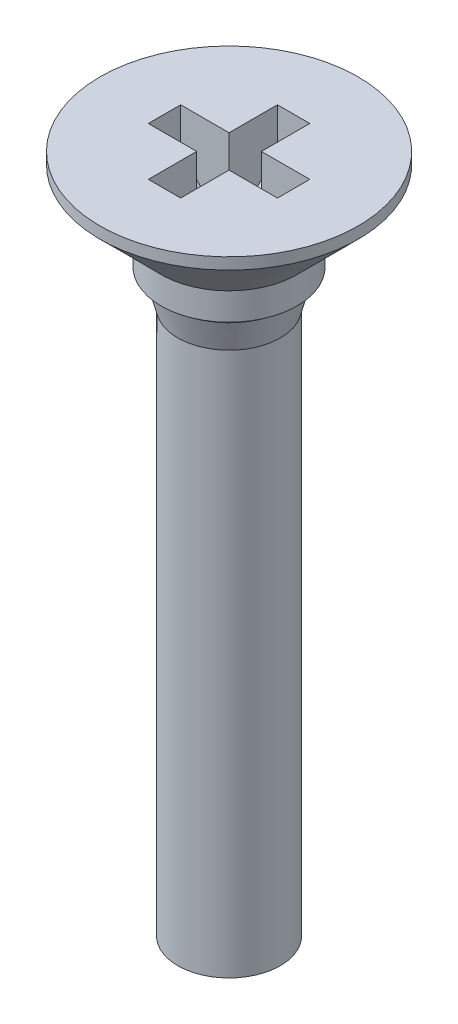
SolidWorks part; units mm, degrees
ref_plane "Vorderseite" through (0, 0, 0) normal (0, 0, 1) x (1, 0, 0)
ref_plane "Oben" through (0, 0, 0) normal (0, 1, 0) x (1, 0, 0)
ref_plane "Rechts" through (0, 0, 0) normal (1, 0, 0) x (0, 0, -1)
sketch "Skizze1" plane through (0, 0, 0) normal (0, 0, 1) x (1, 0, 0)
  line L0 (0, 0) -> (1.9, 0)
  line L1 (1.9, 0) -> (1.9, -0.17)
  line L2 (1.9, -0.17) -> (1, -1.07)
  line L3 (0.87, -1.47) -> (0.87, -1.5689)
  line L4 (0.87, -1.5689) -> (0.7545, -2)
  line L5 (0.7545, -2) -> (0.7545, -10)
  line L6 (0.7545, -10) -> (0, -10)
  line L7 (0, 0) -> (0, -10) construction
  line L8 (0, 0) -> (0, -10)
  line L10 (1, -1.07) -> (1, -1.47)
  line L12 (1, -1.47) -> (0.87, -1.47)
  point P3 (0.87, -1.2)
  dimension "D1" = 45
  dimension "D2" = 15
  dimension "K" = 1.2
  dimension "DA" = 3.8
  dimension "DK" = 1.509
  dimension "L" = 10
  dimension "DG" = 2
  dimension "A" = 0.8
  dimension "DF" = 1.74
  dimension "P" = 0.4
revolve "Basis-Rotation" add sketch "Skizze1" angle 360 about L7
sketch "Skizze2" plane through (0, 0, 0) normal (0, 0, 1) x (1, 0, 0)
  line L0 (0, -1.2) -> (0, 0) construction
  line L1 (0, 0) -> (0, -10) construction
  line L2 (-0.35, -1.2) -> (0.35, -1.2)
  line L3 (0.95, 0) -> (0.95, -0.6)
  line L4 (0.95, -0.6) -> (0.35, -1.2)
  line L5 (0.95, 0) -> (-0.95, 0)
  line L6 (-0.95, -0.6) -> (-0.35, -1.2)
  line L7 (-0.95, 0) -> (-0.95, -0.6)
  line L8 (0, -0.6) -> (0.95, -0.6) construction
  line L9 (1.9, 0) -> (-1.9, 0) construction
  line L11 (1, -1.07) -> (1.9, -0.17) construction
  point P11 (0, 0)
  dimension "M" = 1.9
  dimension "T" = 1.2
extrude "Kreuzschlitz1 H" cut sketch "Skizze2" against normal blind 0.238 and the other way blind 0.238
sketch "Skizze3" plane through (0, 0, 0) normal (1, 0, 0) x (0, 0, -1)
  line L0 (0, -1.2) -> (0, 0) construction
  line L2 (-0.35, -1.2) -> (0.35, -1.2)
  line L3 (0.95, 0) -> (0.95, -0.6)
  line L4 (0.95, -0.6) -> (0.35, -1.2)
  line L5 (0.95, 0) -> (-0.95, 0)
  line L6 (-0.95, -0.6) -> (-0.35, -1.2)
  line L7 (-0.95, 0) -> (-0.95, -0.6)
  line L8 (0, -0.6) -> (0.95, -0.6) construction
  point P11 (0, 0)
extrude "Kreuzschlitz2 H" cut sketch "Skizze3" against normal blind 0.238 and the other way blind 0.238
sketch "Skizze4" plane through (2.4522, 0, -1.8507) normal (0, 1, 0) x (-1, 0, 0)
  line L0 (7.3522, 1.8507) -> (-2.4478, 1.8507) construction
  line L1 (2.4522, -3.0493) -> (2.4522, 6.7507) construction
  line L2 (-2.4478, 1.0342) -> (-2.4478, 2.6672)
  line L3 (-2.4478, 1.0342) -> (0.0059, 1.0342)
  line L4 (0.0059, 1.0342) -> (0.8191, 0.6258)
  line L5 (1.2273, 0.2176) -> (-1.0126, -1.6141)
  line L6 (0.8191, 0.6258) -> (-1.0126, -1.6141)
  line L7 (1.6357, -0.5956) -> (1.2273, 0.2176)
  line L8 (1.6357, -3.0493) -> (1.6357, -0.5956)
  line L9 (1.6357, -3.0493) -> (3.2687, -3.0493)
  line L10 (3.2687, -3.0493) -> (3.2687, -0.5956)
  line L11 (3.2687, -0.5956) -> (3.6772, 0.2176)
  line L12 (2.4522, 1.8507) -> (-1.0126, -1.6141) construction
  line L13 (4.0854, 0.6258) -> (5.917, -1.6141)
  line L14 (3.6772, 0.2176) -> (5.917, -1.6141)
  line L15 (4.8986, 1.0342) -> (4.0854, 0.6258)
  line L16 (7.3522, 1.0342) -> (4.8986, 1.0342)
  line L17 (7.3522, 1.0342) -> (7.3522, 2.6672)
  line L18 (7.3522, 2.6672) -> (4.8986, 2.6672)
  line L19 (4.8986, 2.6672) -> (4.0854, 3.0757)
  line L20 (3.6772, 3.4839) -> (5.917, 5.3156)
  line L21 (4.0854, 3.0757) -> (5.917, 5.3156)
  line L22 (3.2687, 4.2971) -> (3.6772, 3.4839)
  line L23 (3.2687, 6.7507) -> (3.2687, 4.2971)
  line L24 (1.6357, 6.7507) -> (3.2687, 6.7507)
  line L25 (1.6357, 6.7507) -> (1.6357, 4.2971)
  line L26 (1.6357, 4.2971) -> (1.2273, 3.4839)
  line L27 (0.8191, 3.0757) -> (-1.0126, 5.3156)
  line L28 (1.2273, 3.4839) -> (-1.0126, 5.3156)
  line L29 (0.0059, 2.6672) -> (0.8191, 3.0757)
  line L30 (-2.4478, 2.6672) -> (0.0059, 2.6672)
  circle A0 centre (2.4522, 1.8507) radius 4.9 construction
  circle A1 centre (2.4522, 1.8507) radius 2.0415 construction
  circle A2 centre (2.4522, 1.8507) radius 2.579 construction
  dimension "X2" = 4.083
  dimension "X1" = 5.158
  dimension "M" = 9.8
  dimension "D3" = 5.725
  dimension "X3" = 1.633
